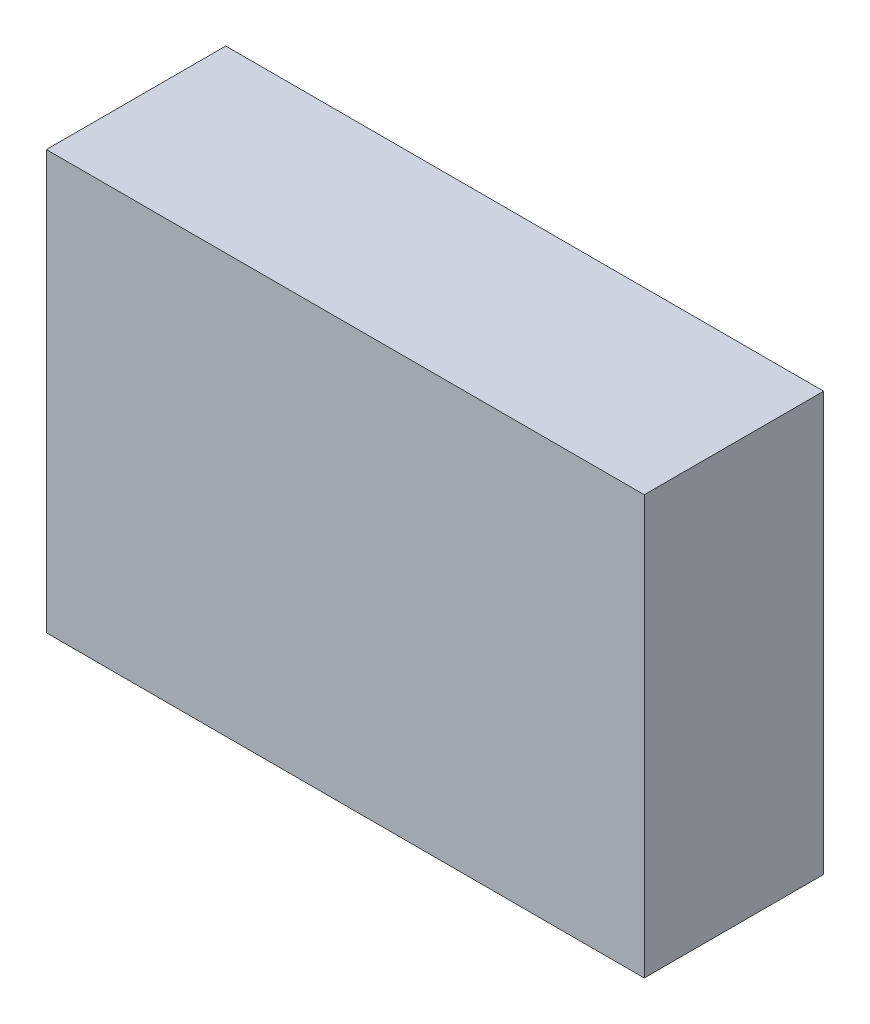
SolidWorks part; units mm, degrees
ref_plane "前基準面" through (0, 0, 0) normal (0, 0, 1) x (1, 0, 0)
ref_plane "上基準面" through (0, 0, 0) normal (0, 1, 0) x (1, 0, 0)
ref_plane "右基準面" through (0, 0, 0) normal (1, 0, 0) x (0, 0, -1)
sketch "草圖1" plane through (0, 0, 0) normal (0, 0, 1) x (1, 0, 0)
  line L1 (-4.8861, 2.7771) -> (95.1139, 2.7771)
  line L2 (-4.8861, 2.7771) -> (-4.8861, -67.2229)
  line L3 (-4.8861, -67.2229) -> (95.1139, -67.2229)
  line L4 (95.1139, 2.7771) -> (95.1139, -67.2229)
  dimension "D1" = 70
  dimension "D2" = 100
extrude "填料-伸長1" add sketch "草圖1" along normal blind 30
